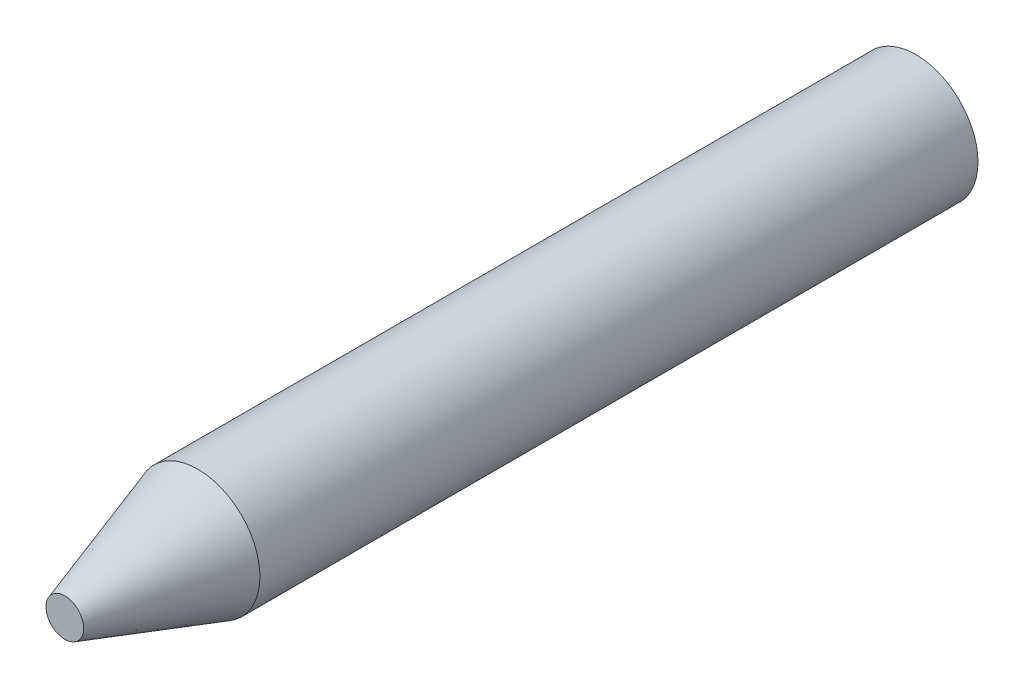
SolidWorks part; units mm, degrees
material "1060 Alloy"
ref_plane "Front Plane" through (0, 0, 0) normal (0, 0, 1) x (1, 0, 0)
ref_plane "Top Plane" through (0, 0, 0) normal (0, 1, 0) x (1, 0, 0)
ref_plane "Right Plane" through (0, 0, 0) normal (1, 0, 0) x (0, 0, -1)
sketch "Sketch1" plane through (0, 0, 0) normal (0, 0, 1) x (1, 0, 0)
  circle A0 centre (0, 0) radius 7
  dimension "D1" = 14
extrude "Boss-Extrude1" add sketch "Sketch1" along normal blind 96
chamfer "Chamfer1" distance 15 angle 18 1 edges at (7, 0, 96)
